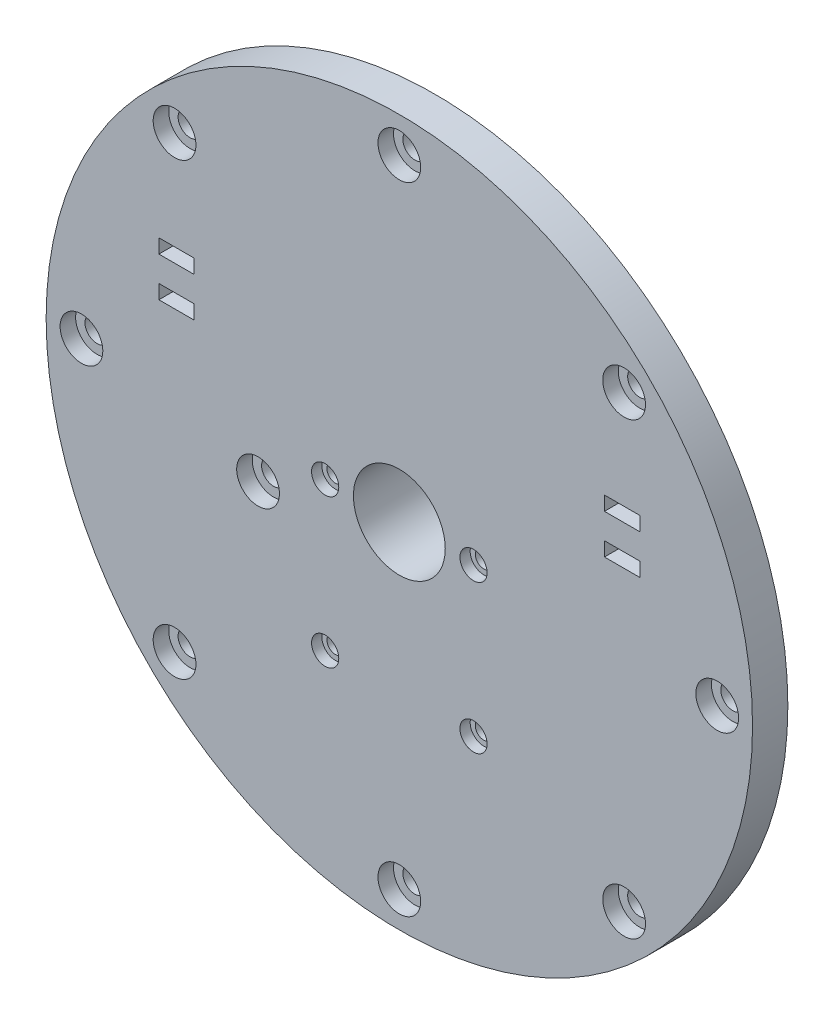
SolidWorks part; units mm, degrees
ref_plane "正面" through (0, 0, 0) normal (0, 0, 1) x (1, 0, 0)
ref_plane "平面" through (0, 0, 0) normal (0, 1, 0) x (1, 0, 0)
ref_plane "右側面" through (0, 0, 0) normal (1, 0, 0) x (0, 0, -1)
sketch "ｽｹｯﾁ1" plane through (0, 0, 0) normal (0, 0, 1) x (1, 0, 0)
  circle A0 centre (0, 0) radius 50
  dimension "D1" = 100
extrude "ﾎﾞｽ - 押し出し1" add sketch "ｽｹｯﾁ1" along normal blind 5
sketch "ｽｹｯﾁ13" plane through (0, 0, 0) normal (0, 0, -1) x (-1, 0, 0)
  line L1 (13, 9) -> (-13, 9)
  line L2 (13, 9) -> (13, -23.5)
  line L3 (13, -23.5) -> (-13, -23.5)
  line L4 (-13, 9) -> (-13, -23.5)
  line L5 (13, 9) -> (-13, -23.5) construction
  line L6 (13, -23.5) -> (-13, 9) construction
  point P0 (0, -7.25)
  point P5 (0, 9)
  dimension "D1" = 32.5
  dimension "D2" = 26
  dimension "D3" = 9
extrude "ﾎﾞｽ - 押し出し3" add sketch "ｽｹｯﾁ13" along normal blind 10
fillet "ﾌｨﾚｯﾄ2" radius 2.5 4 edges at (-13, -23.5, -5) (-13, 9, -5) (13, 9, -5) (13, -23.5, -5)
sketch "ｽｹｯﾁ6" plane through (0, 0, 5) normal (0, 0, 1) x (1, 0, 0)
  circle A0 centre (0, 0) radius 6.5
  dimension "D1" = 13
extrude "ｶｯﾄ - 押し出し1" cut sketch "ｽｹｯﾁ6" against normal through all
hole_wizard "M2 丸平ねじ用座ぐり穴1" positions "ｽｹｯﾁ2" profile "ｽｹｯﾁ3" counterbore size "M2" standard "JIS" end condition through all
sketch "ｽｹｯﾁ2" plane through (0, 0, 5) normal (0, 0, 1) x (1, 0, 0)
  point P0 (-10.5, 0)
  point P4 (-10.5, -21)
  dimension "D1" = 10.5
  dimension "D2" = 10.5
  dimension "D3" = 21
sketch "ｽｹｯﾁ3" plane through (-10.5, 0, 5) normal (1, 0, 0) x (0, -1, 0)
  line L0 (0, 0) -> (0, 15)
  line L1 (0, 15) -> (1.2, 15)
  line L3 (1.2, 15) -> (1.2, 1.45)
  line L4 (1.2, 1.45) -> (1.925, 1.45)
  line L5 (1.925, 1.45) -> (1.925, 0)
  line L7 (1.925, 0) -> (0, 0)
  line L11 (0, -6.35) -> (0, 107.95) construction
  dimension "通し穴の直径" = 2.4
  dimension "通し穴の深さ" = 15
  dimension "座ぐり穴の直径" = 3.85
  dimension "座ぐり穴の深さ" = 1.45
mirror "ﾐﾗｰ1" about plane through (0, 0, 0) normal (1, 0, 0) of "M2 丸平ねじ用座ぐり穴1"
hole_wizard "M3 丸平ねじ用座ぐり穴2" positions "ｽｹｯﾁ4" profile "ｽｹｯﾁ5" counterbore size "M3" standard "JIS" end condition through all
sketch "ｽｹｯﾁ4" plane through (0, 0, 5) normal (0, 0, 1) x (1, 0, 0)
  point P0 (45, 0)
  point P2 (45, 0)
  dimension "D1" = 45
sketch "ｽｹｯﾁ5" plane through (45, 0, 5) normal (1, 0, 0) x (0, -1, 0)
  line L0 (0, 0) -> (0, 15)
  line L1 (0, 15) -> (1.7, 15)
  line L3 (1.7, 15) -> (1.7, 2.2)
  line L4 (1.7, 2.2) -> (3.025, 2.2)
  line L5 (3.025, 2.2) -> (3.025, 0)
  line L7 (3.025, 0) -> (0, 0)
  line L11 (0, -6.35) -> (0, 107.95) construction
  dimension "通し穴の直径" = 3.4
  dimension "通し穴の深さ" = 15
  dimension "座ぐり穴の直径" = 6.05
  dimension "座ぐり穴の深さ" = 2.2
pattern_circular "円形ﾊﾟﾀｰﾝ1" count 8 every 45 about axis through (0, 0, 0) along (0, 0, 1) of "M3 丸平ねじ用座ぐり穴2"
sketch "ｽｹｯﾁ7" plane through (0, 0, 0) normal (0, 0, -1) x (-1, 0, 0)
  line L1 (38.035, 16.25) -> (35.035, 16.25)
  line L2 (38.035, 16.25) -> (38.035, 13.25)
  line L3 (38.035, 13.25) -> (35.035, 13.25)
  line L4 (35.035, 16.25) -> (35.035, 13.25)
  dimension "D1" = 3
  dimension "D2" = 3
  dimension "D3" = 13.25
  dimension "D4" = 35.035
extrude "ﾎﾞｽ - 押し出し2" add sketch "ｽｹｯﾁ7" along normal blind 3
fillet "ﾌｨﾚｯﾄ1" radius 1 1 edges at (-38.035, 14.75, 0)
mirror "ﾐﾗｰ2" about plane through (0, 0, 0) normal (1, 0, 0) of "ﾌｨﾚｯﾄ1", "ﾎﾞｽ - 押し出し2"
sketch "ｽｹｯﾁ10" plane through (0, 0, 0) normal (0, 0, -1) x (-1, 0, 0)
  line L0 (35.035, 16.25) -> (35.035, 13.25) construction
  line L1 (-35.035, 13.25) -> (35.035, 13.25)
  line L2 (-35.035, 13.25) -> (-35.035, 14.85)
  line L3 (-35.035, 14.85) -> (35.035, 14.85)
  line L4 (35.035, 13.25) -> (35.035, 14.85)
  dimension "D1" = 1.6
sketch "ｽｹｯﾁ9" plane through (0, 0, 0) normal (0, 0, -1) x (-1, 0, 0)
  line L0 (35.035, 13.25) -> (39.035, 13.25) construction
  line L1 (34.035, 17.85) -> (29.035, 17.85)
  line L2 (34.035, 17.85) -> (34.035, 15.85)
  line L3 (34.035, 15.85) -> (29.035, 15.85)
  line L4 (29.035, 17.85) -> (29.035, 15.85)
  line L5 (34.035, 12.25) -> (29.035, 12.25)
  line L6 (34.035, 12.25) -> (34.035, 10.25)
  line L7 (34.035, 10.25) -> (29.035, 10.25)
  line L8 (29.035, 12.25) -> (29.035, 10.25)
  line L13 (35.035, 16.25) -> (35.035, 13.25) construction
  line L14 (-35.035, 14.85) -> (35.035, 14.85) construction
  dimension "D1" = 1
  dimension "D2" = 1
  dimension "D3" = 2
  dimension "D4" = 5
  dimension "D5" = 1
extrude "ｶｯﾄ - 押し出し2" cut sketch "ｽｹｯﾁ9" against normal through all
mirror "ﾐﾗｰ3" about plane through (0, 0, 0) normal (1, 0, 0) of "ｶｯﾄ - 押し出し2"
hole_wizard "M3 丸平ねじ用座ぐり穴3" positions "ｽｹｯﾁ11" profile "ｽｹｯﾁ12" counterbore size "M3" standard "JIS" end condition through all
sketch "ｽｹｯﾁ11" plane through (0, 0, 5) normal (0, 0, 1) x (1, 0, 0)
  point P0 (-20, -5)
  dimension "D1" = 5
  dimension "D2" = 20
sketch "ｽｹｯﾁ12" plane through (-20, -5, 5) normal (1, 0, 0) x (0, -1, 0)
  line L0 (0, 0) -> (0, 15)
  line L1 (0, 15) -> (1.7, 15)
  line L3 (1.7, 15) -> (1.7, 2.2)
  line L4 (1.7, 2.2) -> (3.025, 2.2)
  line L5 (3.025, 2.2) -> (3.025, 0)
  line L7 (3.025, 0) -> (0, 0)
  line L11 (0, -6.35) -> (0, 107.95) construction
  dimension "通し穴の直径" = 3.4
  dimension "通し穴の深さ" = 15
  dimension "座ぐり穴の直径" = 6.05
  dimension "座ぐり穴の深さ" = 2.2
